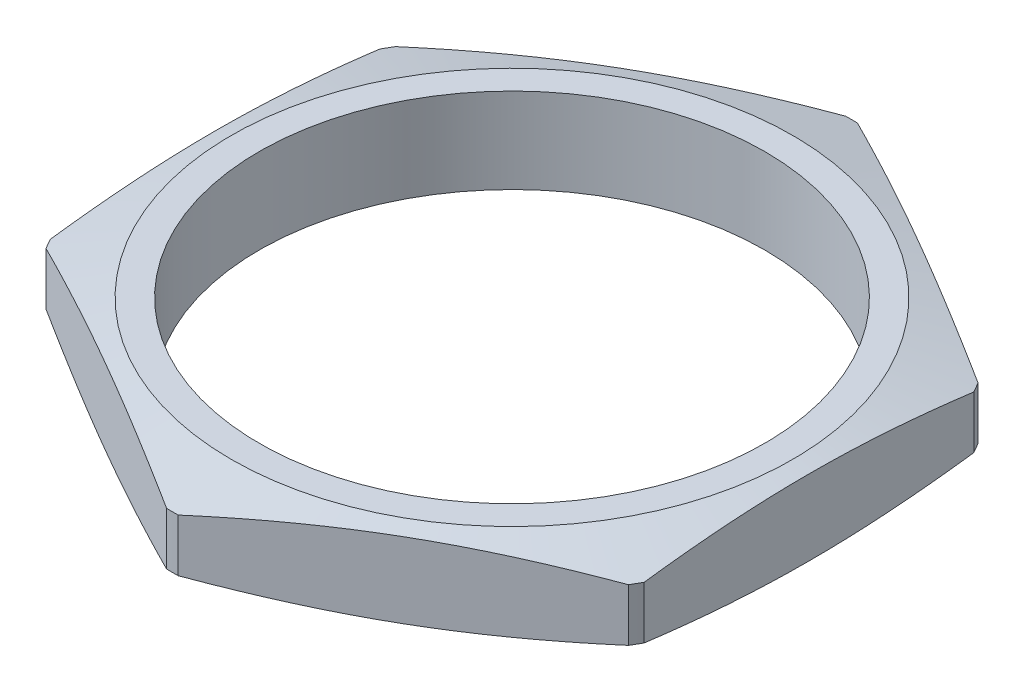
SolidWorks part; units mm, degrees
ref_plane "Front Plane" through (0, 0, 0) normal (0, 0, 1) x (1, 0, 0)
ref_plane "Top Plane" through (0, 0, 0) normal (0, 1, 0) x (1, 0, 0)
ref_plane "Right Plane" through (0, 0, 0) normal (1, 0, 0) x (0, 0, -1)
sketch "Sketch1" plane through (0, 0, 0) normal (0, 1, 0) x (1, 0, 0)
  circle A0 centre (0, 0) radius 10.75
  circle A1 centre (0, 0) radius 8
  dimension "D2" = 16
  dimension "D1" = 21.5
extrude "Boss-Extrude1" add sketch "Sketch1" along normal blind 2.7
chamfer "Chamfer1" distance 0.5 angle 75 1 edges at (0, 2.7, 10.75)
chamfer "Chamfer2" distance 2 angle 15 1 edges at (0, 0, 10.75)
sketch "Sketch3" plane through (0, 2.7, 0) normal (0, 1, 0) x (1, 0, 0)
  line L1 (0, 10.8542) -> (-9.4, 5.4271)
  line L2 (-9.4, 5.4271) -> (-9.4, -5.4271)
  line L3 (-9.4, -5.4271) -> (0, -10.8542)
  line L4 (0, -10.8542) -> (9.4, -5.4271)
  line L5 (9.4, -5.4271) -> (9.4, 5.4271)
  line L6 (9.4, 5.4271) -> (0, 10.8542)
  circle A0 centre (0, 0) radius 9.4 construction
  dimension "D1" = 18.8
extrude "Cut-Extrude1" cut sketch "Sketch3" against normal blind 2.7 flip side to cut
